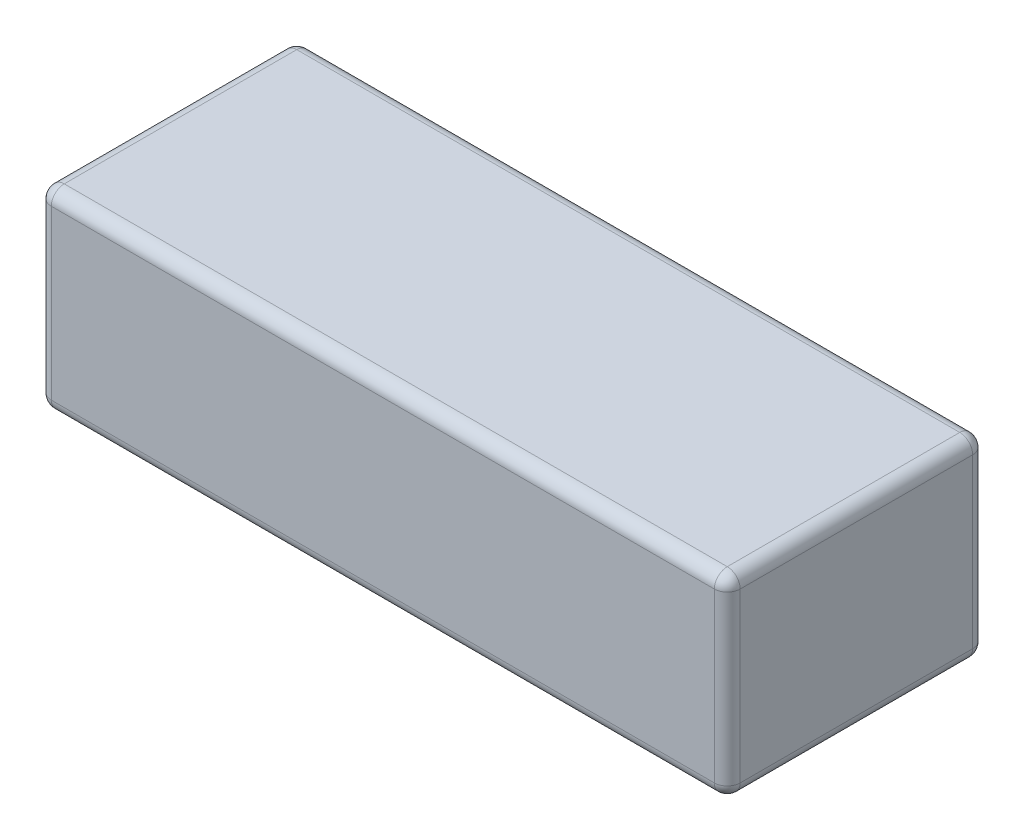
SolidWorks part; units mm, degrees
material "尼龙 6/10"
ref_plane "前视基准面" through (0, 0, 0) normal (0, 0, 1) x (1, 0, 0)
ref_plane "上视基准面" through (0, 0, 0) normal (0, 1, 0) x (1, 0, 0)
ref_plane "右视基准面" through (0, 0, 0) normal (1, 0, 0) x (0, 0, -1)
other "Configuration Table"
sketch "草图1" plane through (0, 0, 0) normal (0, 0, 1) x (1, 0, 0)
  line L1 (0, 0) -> (160, 0)
  line L2 (0, 0) -> (0, -45)
  line L3 (0, -45) -> (160, -45)
  line L4 (160, 0) -> (160, -45)
  dimension "D1" = 160
  dimension "D2" = 45
extrude "凸台-拉伸1" add sketch "草图1" along normal blind 60
fillet "圆角1" radius 3 12 edges at (160, -45, 30) (80, -45, 0) (160, -22.5, 0) (0, -45, 30) (0, -22.5, 0) (160, -22.5, 60) (80, -45, 60) (0, -22.5, 60) (160, 0, 30) (80, 0, 60) (0, 0, 30) (80, 0, 0)
sketch "草图2" plane through (0, 0, 0) normal (0, 1, 0) x (1, 0, 0)
  text T0 "<b>BATTERY</b>" font "黑体" height 3.5
extrude "切除-拉伸1" [suppressed] cut sketch "草图2" against normal blind 1
